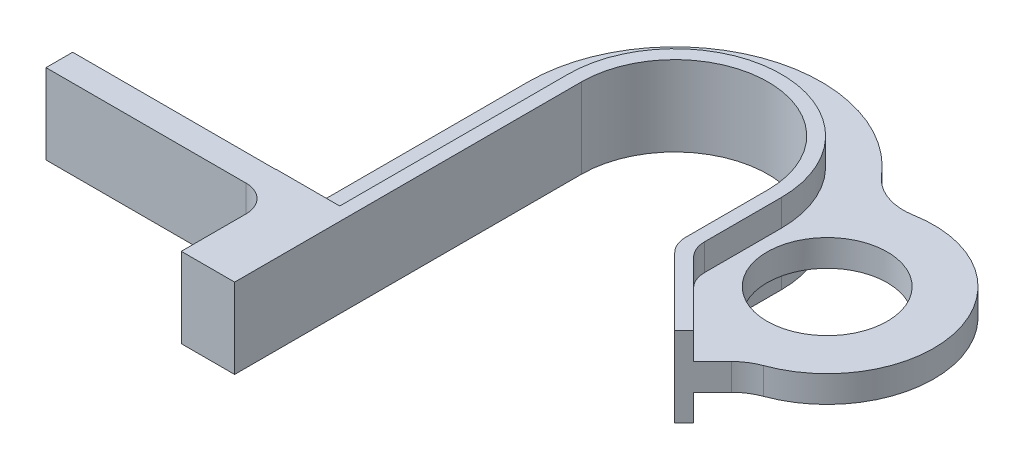
SolidWorks part; units mm, degrees
material "6061-T6 (SS)"
ref_plane "Front Plane" through (0, 0, 0) normal (0, 0, 1) x (1, 0, 0)
ref_plane "Top Plane" through (0, 0, 0) normal (0, 1, 0) x (1, 0, 0)
ref_plane "Right Plane" through (0, 0, 0) normal (1, 0, 0) x (0, 0, -1)
sketch "Sketch1" plane through (0, 0, 0) normal (0, 1, 0) x (1, 0, 0)
  line L0 (-22.225, 0) -> (-22.225, -82.55)
  line L1 (-22.225, -82.55) -> (-34.925, -82.55)
  line L2 (-34.925, -82.55) -> (-34.925, 0)
  line L3 (34.925, 0) -> (34.925, -16.9645)
  line L4 (22.225, -22.225) -> (40.1855, -40.1855)
  line L5 (22.225, -22.225) -> (22.225, 0)
  line L6 (40.1855, -40.1855) -> (49.1658, -31.2053)
  line L7 (49.1658, -31.2053) -> (34.925, -16.9645)
  arc A0 (22.225, 0) -> (-22.225, 0) centre (0, 0) ccw
  arc A1 (34.925, 0) -> (-34.925, 0) centre (0, 0) ccw
  dimension "D1" = 44.45
  dimension "D2" = 12.7
  dimension "D3" = 12.7
  dimension "D4" = 82.55
  dimension "D5" = 22.225
  dimension "D6" = 25.4
  dimension "D7" = 90
  dimension "D8" = 135
extrude "Boss-Extrude1" add sketch "Sketch1" along normal blind 19.05
sketch "Sketch3" plane through (0, 19.05, 0) normal (0, 1, 0) x (1, 0, 0)
  line L0 (-34.925, 0) -> (-34.925, -82.55) construction
  line L1 (34.925, -16.9645) -> (34.925, 0) construction
  line L2 (49.1658, -31.2053) -> (34.925, -16.9645) construction
  line L3 (-34.925, 0) -> (-34.925, -82.55)
  line L4 (34.925, -16.9645) -> (34.925, 0)
  line L5 (49.1658, -31.2053) -> (34.925, -16.9645)
  line L6 (42.4306, -37.9404) -> (25.4, -20.9099)
  line L7 (25.4, -20.9099) -> (25.4, 0)
  line L8 (-25.4, 0) -> (-25.4, -82.55)
  line L9 (42.4306, -37.9404) -> (49.1658, -31.2053)
  line L10 (-34.925, -82.55) -> (-25.4, -82.55)
  arc A0 (34.925, 0) -> (-34.925, 0) centre (0, 0) ccw construction
  arc A1 (34.925, 0) -> (-34.925, 0) centre (0, 0) ccw
  arc A2 (25.4, 0) -> (-25.4, 0) centre (0, 0) ccw
  dimension "D1" = 9.525
extrude "Cut-Extrude3" cut sketch "Sketch3" against normal blind 6.35
ref_plane "Plane1" through (0, 9.525, 0) normal (0, 1, 0) x (1, 0, 0)
mirror "Mirror1" about plane through (0, 9.525, 0) normal (0, 1, 0) of "Cut-Extrude3"
fillet "Fillet1" radius 6.35 3 edges at (25.4, 3.175, 20.9099) (25.4, 15.875, 20.9099) (34.925, 9.525, 16.9645)
fillet "Fillet2" radius 6.35 1 edges at (22.225, 9.525, 22.225)
sketch "Sketch4" plane through (-25.4, 0, 0) normal (-1, 0, 0) x (0, 0, 1)
  line L0 (82.55, 19.05) -> (0, 19.05) construction
  line L1 (60.7822, 19.05) -> (54.4322, 19.05)
  line L2 (60.7822, 19.05) -> (60.7822, 0)
  line L3 (60.7822, 0) -> (54.4322, 0)
  line L4 (54.4322, 19.05) -> (54.4322, 0)
  line L5 (82.55, 0) -> (0, 0) construction
  line L6 (82.55, 6.35) -> (82.55, 0) construction
  dimension "D1" = 6.35
  dimension "D2" = 21.7678
extrude "Boss-Extrude2" add sketch "Sketch4" along normal blind 63.5
sketch "Sketch6" plane through (0, 0, 82.55) normal (0, 0, 1) x (1, 0, 0)
  line L0 (-88.9, 0) -> (-25.4, 0) construction
  line L1 (-22.225, 19.05) -> (-34.925, 19.05)
  line L2 (-22.225, 19.05) -> (-22.225, 0)
  line L3 (-22.225, 0) -> (-34.925, 0)
  line L4 (-34.925, 19.05) -> (-34.925, 0)
  line L5 (-34.925, 6.35) -> (-34.925, 12.7) construction
extrude "Boss-Extrude3" add sketch "Sketch6" against normal blind 28.194
fillet "Fillet4" radius 6.35 1 edges at (-34.925, 9.525, 60.7822)
fillet "Fillet5" radius 6.35 1 edges at (-34.925, 9.525, 54.4322)
sketch "Sketch7" plane through (0, 0, 82.55) normal (0, 0, 1) x (1, 0, 0)
  line L1 (-34.925, 19.05) -> (-22.225, 19.05)
  line L2 (-34.925, 19.05) -> (-34.925, 0)
  line L3 (-34.925, 0) -> (-22.225, 0)
  line L4 (-22.225, 19.05) -> (-22.225, 0)
sketch "Sketch8" plane through (0, 12.7, 0) normal (0, 1, 0) x (1, 0, 0)
  line L0 (34.925, -14.3342) -> (34.925, 0) construction
  line L1 (49.1658, -31.2053) -> (36.7849, -18.8244) construction
  line L2 (34.925, -14.3342) -> (34.925, 0)
  line L3 (49.1658, -31.2053) -> (36.7849, -18.8244)
  arc A0 (49.1658, -31.2053) -> (31.0939, 15.9036) centre (42.8841, -6.5943) ccw
  arc A1 (34.925, -14.3342) -> (36.7849, -18.8244) centre (41.275, -14.3342) ccw construction
  arc A3 (22.225, -19.5947) -> (24.0849, -24.0849) centre (28.575, -19.5947) ccw construction
  arc A4 (34.925, -14.3342) -> (36.7849, -18.8244) centre (41.275, -14.3342) ccw
  arc A5 (34.925, 0) -> (-34.925, 0) centre (0, 0) ccw construction
  arc A6 (34.925, 0) -> (31.0939, 15.9036) centre (0, 0) ccw
  point P10 (22.7084, -22.0248)
  dimension "D1" = 50.8
  dimension "D2" = 25.4
extrude "Boss-Extrude4" add sketch "Sketch8" against normal blind 6.35
fillet "Fillet6" radius 12.7 1 edges at (31.0939, 9.525, -15.9036)
fillet "Fillet7" radius 12.7 1 edges at (49.1658, 9.525, 31.2053)
sketch "Sketch9" plane through (0, 12.7, 0) normal (0, 1, 0) x (1, 0, 0)
  line L0 (25.4, 0) -> (25.4, -18.2796) construction
  circle A0 centre (42.8841, -6.5943) radius 14.3091
  arc A1 (51.5923, -30.4548) -> (38.4438, 18.4146) centre (42.8841, -6.5943) ccw construction
  point P5 (28.575, -6.5943)
  dimension "D1" = 3.175
extrude "Cut-Extrude5" cut sketch "Sketch9" against normal through all contours A0
